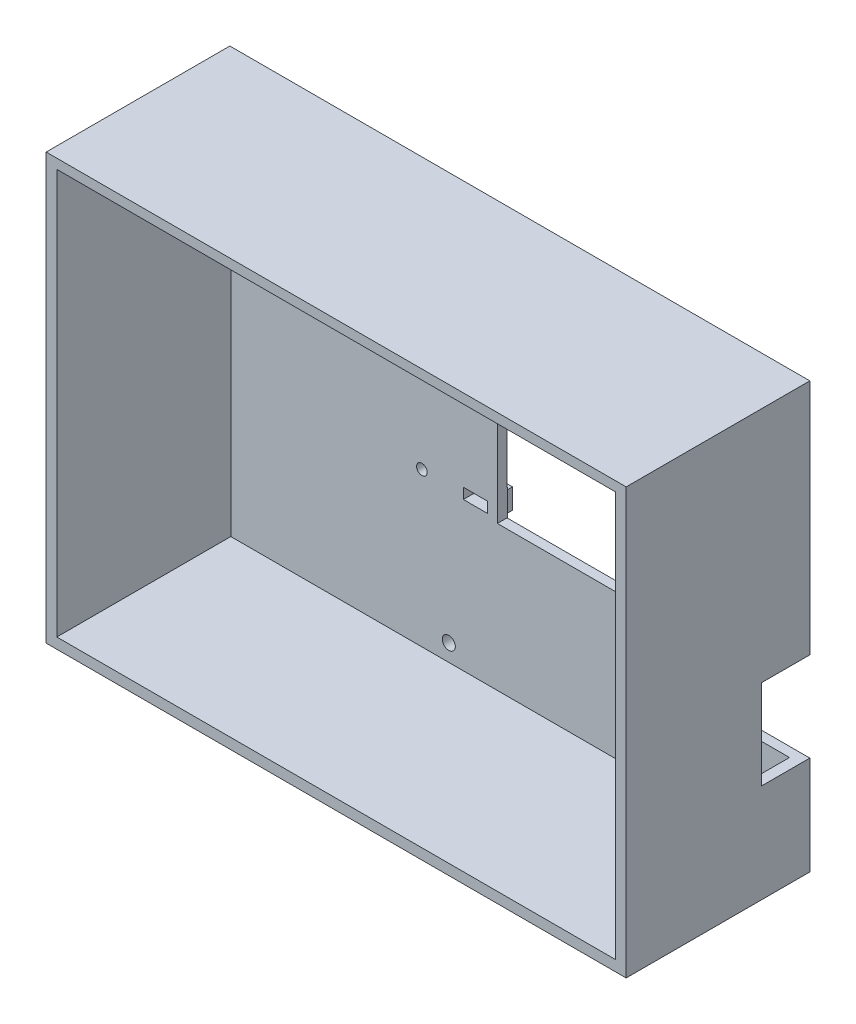
SolidWorks part; units mm, degrees
ref_plane "前视基准面" through (0, 0, 0) normal (0, 0, 1) x (1, 0, 0)
ref_plane "上视基准面" through (0, 0, 0) normal (0, 1, 0) x (1, 0, 0)
ref_plane "右视基准面" through (0, 0, 0) normal (1, 0, 0) x (0, 0, -1)
sketch "草图1" plane through (0, 0, 0) normal (0, 0, 1) x (1, 0, 0)
  line L1 (-523.1068, 343.1867) -> (-403.1068, 343.1867)
  line L2 (-523.1068, 343.1867) -> (-523.1068, 263.1867)
  line L3 (-523.1068, 263.1867) -> (-403.1068, 263.1867)
  line L4 (-403.1068, 343.1867) -> (-403.1068, 263.1867)
  dimension "D1" = 80
  dimension "D2" = 120
extrude "凸台-拉伸1" add sketch "草图1" along normal blind 38
sketch "草图3" plane through (0, 0, 38) normal (0, 0, 1) x (1, 0, 0)
  line L8 (-521.9068, 341.9867) -> (-521.9068, 264.3867)
  line L9 (-521.9068, 264.3867) -> (-404.3068, 264.3867)
  line L10 (-404.3068, 264.3867) -> (-404.3068, 341.9867)
  line L11 (-404.3068, 341.9867) -> (-521.9068, 341.9867)
  line L12 (-521.9068, 341.9867) -> (-521.9068, 264.3867)
  line L13 (-521.9068, 264.3867) -> (-404.3068, 264.3867)
  line L14 (-404.3068, 264.3867) -> (-404.3068, 341.9867)
  line L15 (-404.3068, 341.9867) -> (-521.9068, 341.9867)
  dimension "D1" = 1.2
extrude "切除-拉伸1" cut sketch "草图3" against normal blind 36
sketch "草图4" plane through (0, 0, 0) normal (0, 0, -1) x (-1, 0, 0)
  line L1 (424.5012, 301.0883) -> (399.3482, 301.0883)
  line L2 (424.5012, 301.0883) -> (424.5012, 282.5954)
  line L3 (424.5012, 282.5954) -> (399.3482, 282.5954)
  line L4 (399.3482, 301.0883) -> (399.3482, 282.5954)
extrude "切除-拉伸2" cut sketch "草图4" against normal blind 10
sketch "草图7" plane through (0, 0, 0) normal (0, 0, -1) x (-1, 0, 0)
  line L16 (460.9068, 319.1867) -> (481.5688, 319.1867) construction
  line L17 (465.7551, 319.1867) -> (483.1688, 319.1867)
  line L18 (465.7551, 319.1867) -> (465.7551, 314.1101)
  line L19 (465.7551, 314.1101) -> (483.1688, 314.1101)
  line L20 (483.1688, 319.1867) -> (483.1688, 314.1101)
  line L21 (483.1688, 317.5867) -> (483.1688, 295.7867) construction
  line L22 (481.5688, 294.1867) -> (460.9068, 294.1867) construction
  line L23 (465.7551, 294.1867) -> (483.1688, 294.1867)
  line L24 (465.7551, 294.1867) -> (465.7551, 299.7285)
  line L25 (465.7551, 299.7285) -> (483.1688, 299.7285)
  line L26 (483.1688, 294.1867) -> (483.1688, 299.7285)
extrude "凸台-拉伸2" add sketch "草图7" along normal blind 0.1
ref_plane "基准面1" through (-465.7551, 319.1867, -0.1) normal (0, 0, 1) x (1, 0, 0)
sketch "草图9" plane through (0, 0, 0) normal (0, 0, -1) x (-1, 0, 0)
  line L1 (465.7551, 319.1867) -> (437.8723, 319.1867)
  line L2 (465.7551, 319.1867) -> (465.7551, 294.3082)
  line L3 (465.7551, 294.3082) -> (437.8723, 294.3082)
  line L4 (437.8723, 319.1867) -> (437.8723, 294.3082)
extrude "切除-拉伸4" cut sketch "草图9" against normal blind 12
ref_plane "基准面2" through (0, 303.1867, 0) normal (0, 1, 0) x (1, 0, 0)
sketch "草图12" plane through (0, 0, -0.1) normal (0, 0, -1) x (-1, 0, 0)
  line L1 (467.7688, 318.4867) -> (472.7938, 318.4867)
  line L2 (467.7688, 318.4867) -> (467.7688, 316.2867)
  line L3 (467.7688, 316.2867) -> (472.7938, 316.2867)
  line L4 (472.7938, 318.4867) -> (472.7938, 316.2867)
  line L5 (467.7688, 297.2867) -> (472.7938, 297.2867)
  line L6 (467.7688, 297.2867) -> (467.7688, 295.0867)
  line L7 (467.7688, 295.0867) -> (472.7938, 295.0867)
  line L8 (472.7938, 297.2867) -> (472.7938, 295.0867)
  circle A0 centre (481.3688, 317.3867) radius 1.0852
  circle A1 centre (481.3688, 296.1867) radius 1.1
extrude "切除-拉伸5" cut sketch "草图12" against normal blind 12
sketch "草图13" plane through (0, 0, 2) normal (0, 0, 1) x (1, 0, 0)
  circle A0 centre (-475.8068, 316.8867) radius 1.35
  circle A1 centre (-417.8068, 316.8867) radius 1.35
  circle A2 centre (-417.8068, 267.8867) radius 1.35
  circle A3 centre (-475.8068, 267.8867) radius 1.35
extrude "切除-拉伸6" cut sketch "草图13" against normal blind 12
sketch "草图14" plane through (0, 341.9867, 0) normal (0, -1, 0) x (1, 0, 0)
  line L4 (-404.3068, 38) -> (-521.9068, 38)
  line L5 (-521.9068, 38) -> (-521.9068, 2)
  line L6 (-521.9068, 2) -> (-404.3068, 2)
  line L7 (-404.3068, 2) -> (-404.3068, 38)
  line L8 (-404.3068, 38) -> (-521.9068, 38)
  line L9 (-521.9068, 38) -> (-521.9068, 2)
  line L10 (-521.9068, 2) -> (-404.3068, 2)
  line L11 (-404.3068, 2) -> (-404.3068, 38)
  dimension "D1" = 0
extrude "切除-拉伸7" cut sketch "草图14" against normal blind 10
sketch "草图15" plane through (0, 343.1867, 0) normal (0, 1, 0) x (1, 0, 0)
  line L8 (-521.9068, -2) -> (-404.3068, -2)
  line L9 (-404.3068, -2) -> (-404.3068, -38)
  line L10 (-404.3068, -38) -> (-403.1068, -38)
  line L11 (-403.1068, -38) -> (-403.1068, 0)
  line L12 (-403.1068, 0) -> (-523.1068, 0)
  line L13 (-523.1068, 0) -> (-523.1068, -38)
  line L14 (-523.1068, -38) -> (-521.9068, -38)
  line L15 (-521.9068, -38) -> (-521.9068, -2)
  line L16 (-521.9068, -2) -> (-404.3068, -2)
  line L17 (-404.3068, -2) -> (-404.3068, -38)
  line L18 (-404.3068, -38) -> (-403.1068, -38)
  line L19 (-403.1068, -38) -> (-403.1068, 0)
  line L20 (-403.1068, 0) -> (-523.1068, 0)
  line L21 (-523.1068, 0) -> (-523.1068, -38)
  line L22 (-523.1068, -38) -> (-521.9068, -38)
  line L23 (-521.9068, -38) -> (-521.9068, -2)
  dimension "D1" = 0
extrude "凸台-拉伸3" add sketch "草图15" along normal blind 5
sketch "草图16" plane through (0, 348.1867, 0) normal (0, 1, 0) x (1, 0, 0)
  line L1 (-403.1068, 0) -> (-523.1068, 0)
  line L2 (-403.1068, 0) -> (-403.1068, -38)
  line L3 (-403.1068, -38) -> (-523.1068, -38)
  line L4 (-523.1068, 0) -> (-523.1068, -38)
extrude "凸台-拉伸4" add sketch "草图16" along normal blind 2
sketch "草图17" plane through (-521.9068, 0, 0) normal (1, 0, 0) x (0, 0, -1)
  line L4 (-38, 348.1867) -> (-38, 264.3867)
  line L5 (-38, 264.3867) -> (-2, 264.3867)
  line L6 (-2, 264.3867) -> (-2, 348.1867)
  line L7 (-2, 348.1867) -> (-38, 348.1867)
  line L8 (-38, 348.1867) -> (-38, 264.3867)
  line L9 (-38, 264.3867) -> (-2, 264.3867)
  line L10 (-2, 264.3867) -> (-2, 348.1867)
  line L11 (-2, 348.1867) -> (-38, 348.1867)
  dimension "D1" = 0
extrude "凸台-拉伸5" add sketch "草图17" along normal blind 1
sketch "草图18" plane through (-404.3068, 0, 0) normal (-1, 0, 0) x (0, 0, 1)
  line L8 (10, 301.0883) -> (10, 282.5954)
  line L9 (10, 282.5954) -> (2, 282.5954)
  line L10 (2, 282.5954) -> (2, 264.3867)
  line L11 (2, 264.3867) -> (38, 264.3867)
  line L12 (38, 264.3867) -> (38, 348.1867)
  line L13 (38, 348.1867) -> (2, 348.1867)
  line L14 (2, 348.1867) -> (2, 301.0883)
  line L15 (2, 301.0883) -> (10, 301.0883)
  line L16 (10, 301.0883) -> (10, 282.5954)
  line L17 (10, 282.5954) -> (2, 282.5954)
  line L18 (2, 282.5954) -> (2, 264.3867)
  line L19 (2, 264.3867) -> (38, 264.3867)
  line L20 (38, 264.3867) -> (38, 348.1867)
  line L21 (38, 348.1867) -> (2, 348.1867)
  line L22 (2, 348.1867) -> (2, 301.0883)
  line L23 (2, 301.0883) -> (10, 301.0883)
  dimension "D1" = 0
extrude "凸台-拉伸6" add sketch "草图18" along normal blind 1
sketch "草图19" plane through (0, 263.1867, 0) normal (0, -1, 0) x (1, 0, 0)
  line L4 (-523.1068, 0) -> (-403.1068, 0)
  line L5 (-403.1068, 0) -> (-403.1068, 38)
  line L6 (-403.1068, 38) -> (-523.1068, 38)
  line L7 (-523.1068, 38) -> (-523.1068, 0)
  line L8 (-523.1068, 0) -> (-403.1068, 0)
  line L9 (-403.1068, 0) -> (-403.1068, 38)
  line L10 (-403.1068, 38) -> (-523.1068, 38)
  line L11 (-523.1068, 38) -> (-523.1068, 0)
  dimension "D1" = 0
extrude "凸台-拉伸7" add sketch "草图19" along normal blind 1
sketch "草图20" plane through (0, 0, -0.1) normal (0, 0, -1) x (-1, 0, 0)
  line L0 (467.7688, 295.0867) -> (472.7938, 295.0867) construction
  line L5 (467.7688, 297.2867) -> (467.7688, 295.0867) construction
  line L6 (472.7938, 297.2867) -> (467.7688, 297.2867) construction
  line L7 (466.7952, 319.4867) -> (473.9952, 319.4867)
  line L8 (466.7952, 319.4867) -> (466.7952, 315.2867)
  line L9 (466.7952, 315.2867) -> (473.9952, 315.2867)
  line L10 (473.9952, 319.4867) -> (473.9952, 315.2867)
  line L11 (466.7952, 319.4867) -> (473.9952, 315.2867) construction
  line L12 (466.7952, 315.2867) -> (473.9952, 319.4867) construction
  line L13 (472.7938, 318.4867) -> (467.7688, 318.4867) construction
  line L14 (467.7688, 316.2867) -> (472.7938, 316.2867) construction
  line L15 (466.7254, 298.3339) -> (473.9254, 298.3339)
  line L16 (466.7254, 298.3339) -> (466.7254, 294.1339)
  line L17 (466.7254, 294.1339) -> (473.9254, 294.1339)
  line L18 (473.9254, 298.3339) -> (473.9254, 294.1339)
  line L19 (466.7254, 298.3339) -> (473.9254, 294.1339) construction
  line L20 (466.7254, 294.1339) -> (473.9254, 298.3339) construction
  line L21 (472.7938, 295.0867) -> (472.7938, 297.2867) construction
  line L22 (467.7688, 318.4867) -> (467.7688, 316.2867) construction
  line L23 (472.7938, 316.2867) -> (472.7938, 318.4867) construction
  line L24 (467.7688, 295.0867) -> (472.7938, 295.0867)
  line L25 (467.7688, 297.2867) -> (467.7688, 295.0867)
  line L26 (472.7938, 297.2867) -> (467.7688, 297.2867)
  line L27 (472.7938, 295.0867) -> (472.7938, 297.2867)
  line L28 (467.7688, 316.2867) -> (472.7938, 316.2867)
  line L29 (467.7688, 318.4867) -> (467.7688, 316.2867)
  line L30 (472.7938, 318.4867) -> (467.7688, 318.4867)
  line L31 (472.7938, 316.2867) -> (472.7938, 318.4867)
  circle A0 centre (481.3688, 317.3867) radius 2
  circle A1 centre (481.3688, 296.1867) radius 1.1 construction
  circle A2 centre (481.3688, 296.1867) radius 2.0016
  circle A3 centre (481.3688, 317.3867) radius 1.0852 construction
  circle A4 centre (481.3688, 296.1867) radius 1.1
  circle A5 centre (481.3688, 317.3867) radius 1.0852
  point P3 (470.3952, 317.3867)
  point P11 (470.3952, 317.3867)
  point P16 (0, 0)
  point P17 (470.3254, 296.2339)
  dimension "D1" = 4
  dimension "D2" = 7.2
  dimension "D3" = 1
  dimension "D4" = 1
  dimension "D5" = 7.2
extrude "凸台-拉伸8" add sketch "草图20" along normal blind 2
